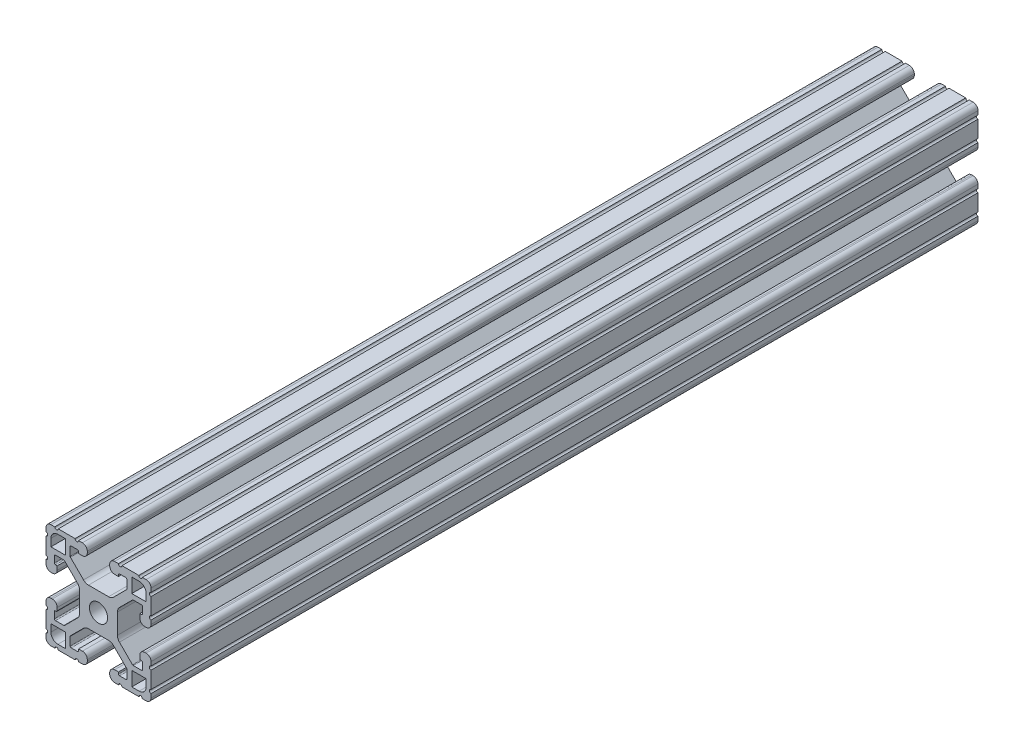
SolidWorks part; units mm, degrees
ref_plane "Front Plane" through (0, 0, 0) normal (0, 0, 1) x (1, 0, 0)
ref_plane "Top Plane" through (0, 0, 0) normal (0, 1, 0) x (1, 0, 0)
ref_plane "Right Plane" through (0, 0, 0) normal (1, 0, 0) x (0, 0, -1)
sketch "Sketch1" plane through (0, 0, 0) normal (0, 0, 1) x (1, 0, 0)
  line L0 (0, -19.05) -> (0, 19.05) construction
  line L1 (19.05, 0) -> (-19.05, 0) construction
  line L2 (4.064, 19.05) -> (-4.064, 19.05) construction
  line L3 (0, -6.858) -> (0, 6.858) construction
  line L4 (-4.064, 19.05) -> (-4.064, 14.986) construction
  line L5 (19.05, -10.287) -> (19.05, 10.287) construction
  line L6 (0, -3.302) -> (0, 3.302) construction
  point P4 (0, 0)
  point P8 (0, 0)
  point P11 (0, 19.05)
  point P14 (0, 0)
  point P18 (19.05, 0)
  point P21 (0, 0)
  dimension "Rail Width" = 38.1
  dimension "Rail Height" = 38.1
  dimension "T-Slot Width" = 8.128
  dimension "Thickness" = 4.064
  dimension "Opening Width" = 20.574
  dimension "Center Hole Diameter" = 6.604
  dimension "Slot Depth" = 12.192
sketch "Sketch2" plane through (0, 0, 0) normal (1, 0, 0) x (0, 0, -1)
  line L0 (-150.0188, 0) -> (150.0188, 0) construction
  line L1 (0, 19.05) -> (0, -19.05) construction
  line L2 (-25.4, 19.05) -> (25.4, 19.05) construction
  line L4 (3048, -19.05) -> (-3048, -19.05) construction
  point P0 (99.2188, 0)
  point P3 (-99.2188, 0)
  point P4 (0, 0)
  dimension "D1" = 50.8
  dimension "Rep Length" = 300.0375
  dimension "D2" = 50.8
  dimension "Length Range [Min]" = 50.8
  dimension "Length Range [Max]" = 6096
sketch "Sketch3" plane through (0, 0, 0) normal (0, 0, 1) x (1, 0, 0)
  line L1 (19.05, -19.05) -> (-19.05, -19.05)
  line L2 (19.05, -19.05) -> (19.05, 19.05)
  line L3 (19.05, 19.05) -> (-19.05, 19.05)
  line L4 (-19.05, -19.05) -> (-19.05, 19.05)
  line L5 (19.05, -19.05) -> (-19.05, 19.05) construction
  line L6 (19.05, 19.05) -> (-19.05, -19.05) construction
  point P0 (0, 0)
extrude "Boss-Extrude1" add sketch "Sketch3" along normal up to vertex (150.0188 mm away) and the other way up to vertex (150.0188 mm away) up to point (0, 0, 150.0188) other way up to point (0, 0, -150.0188)
sketch "Sketch4" plane through (0, 0, 150.0188) normal (0, 0, 1) x (1, 0, 0)
  line L4 (4.064, 14.986) -> (4.064, 19.05)
  line L5 (7.239, 14.986) -> (4.064, 14.986)
  line L6 (19.05, 0) -> (-19.05, 0) construction
  line L7 (4.7027, 6.858) -> (-4.7027, 6.858)
  line L8 (-4.7027, 6.858) -> (-10.287, 12.4423)
  line L37 (-19.05, 19.05) -> (-19.05, -19.05) construction
  line L38 (-19.05, -19.05) -> (19.05, -19.05) construction
  line L39 (-10.287, 12.4423) -> (-10.287, 16.002)
  line L40 (-10.287, 16.002) -> (-7.239, 16.002)
  line L41 (-7.239, 16.002) -> (-7.239, 14.986)
  line L42 (-7.239, 14.986) -> (-4.064, 14.986)
  line L43 (-4.064, 14.986) -> (-4.064, 19.05)
  line L44 (-4.064, 19.05) -> (4.064, 19.05)
  line L45 (0, 19.05) -> (0, 0) construction
  line L46 (-19.05, 19.05) -> (0, 0) construction
  line L47 (7.239, 16.002) -> (7.239, 14.986)
  line L48 (10.287, 16.002) -> (7.239, 16.002)
  line L49 (10.287, 12.4423) -> (10.287, 16.002)
  line L50 (4.7027, 6.858) -> (10.287, 12.4423)
  line L51 (-19.05, 0) -> (19.05, 0) construction
  line L52 (4.7027, -6.858) -> (10.287, -12.4423)
  line L53 (10.287, -12.4423) -> (10.287, -16.002)
  line L54 (10.287, -16.002) -> (7.239, -16.002)
  line L55 (7.239, -16.002) -> (7.239, -14.986)
  line L56 (-4.064, -19.05) -> (4.064, -19.05)
  line L57 (-4.064, -14.986) -> (-4.064, -19.05)
  line L58 (-7.239, -14.986) -> (-4.064, -14.986)
  line L59 (-7.239, -16.002) -> (-7.239, -14.986)
  line L60 (-10.287, -16.002) -> (-7.239, -16.002)
  line L61 (-10.287, -12.4423) -> (-10.287, -16.002)
  line L62 (-4.7027, -6.858) -> (-10.287, -12.4423)
  line L63 (4.7027, -6.858) -> (-4.7027, -6.858)
  line L64 (7.239, -14.986) -> (4.064, -14.986)
  line L65 (4.064, -14.986) -> (4.064, -19.05)
  line L66 (-6.858, -4.7027) -> (-12.4423, -10.287)
  line L67 (-12.4423, -10.287) -> (-16.002, -10.287)
  line L68 (-16.002, -10.287) -> (-16.002, -7.239)
  line L69 (-16.002, -7.239) -> (-14.986, -7.239)
  line L70 (-19.05, 4.064) -> (-19.05, -4.064)
  line L71 (-14.986, 4.064) -> (-19.05, 4.064)
  line L72 (-14.986, 7.239) -> (-14.986, 4.064)
  line L73 (-16.002, 7.239) -> (-14.986, 7.239)
  line L74 (-16.002, 10.287) -> (-16.002, 7.239)
  line L75 (-12.4423, 10.287) -> (-16.002, 10.287)
  line L76 (-6.858, 4.7027) -> (-12.4423, 10.287)
  line L77 (-6.858, -4.7027) -> (-6.858, 4.7027)
  line L78 (-14.986, -7.239) -> (-14.986, -4.064)
  line L79 (-14.986, -4.064) -> (-19.05, -4.064)
  line L80 (14.986, -4.064) -> (19.05, -4.064)
  line L81 (14.986, -7.239) -> (14.986, -4.064)
  line L82 (6.858, -4.7027) -> (6.858, 4.7027)
  line L83 (6.858, 4.7027) -> (12.4423, 10.287)
  line L84 (12.4423, 10.287) -> (16.002, 10.287)
  line L85 (16.002, 10.287) -> (16.002, 7.239)
  line L86 (16.002, 7.239) -> (14.986, 7.239)
  line L87 (14.986, 7.239) -> (14.986, 4.064)
  line L88 (14.986, 4.064) -> (19.05, 4.064)
  line L89 (19.05, 4.064) -> (19.05, -4.064)
  line L90 (16.002, -7.239) -> (14.986, -7.239)
  line L91 (16.002, -10.287) -> (16.002, -7.239)
  line L92 (12.4423, -10.287) -> (16.002, -10.287)
  line L93 (6.858, -4.7027) -> (12.4423, -10.287)
  line L94 (19.05, -19.05) -> (19.05, 19.05) construction
  line L95 (12.065, 17.272) -> (17.272, 17.272)
  line L96 (12.065, 17.272) -> (12.065, 12.065)
  line L97 (12.065, 12.065) -> (17.272, 12.065)
  line L98 (17.272, 17.272) -> (17.272, 12.065)
  line L99 (19.05, 19.05) -> (-19.05, 19.05) construction
  line L100 (17.272, -17.272) -> (17.272, -12.065)
  line L101 (12.065, -17.272) -> (17.272, -17.272)
  line L102 (12.065, -17.272) -> (12.065, -12.065)
  line L103 (12.065, -12.065) -> (17.272, -12.065)
  line L104 (-17.272, 17.272) -> (-17.272, 12.065)
  line L105 (-12.065, 12.065) -> (-17.272, 12.065)
  line L106 (-12.065, 17.272) -> (-12.065, 12.065)
  line L107 (-12.065, 17.272) -> (-17.272, 17.272)
  line L108 (-12.065, -12.065) -> (-17.272, -12.065)
  line L109 (-12.065, -17.272) -> (-12.065, -12.065)
  line L110 (-12.065, -17.272) -> (-17.272, -17.272)
  line L111 (-17.272, -17.272) -> (-17.272, -12.065)
  circle A5 centre (0, 0) radius 3.302
  point P21 (0, 6.858)
  point P23 (0, -6.858)
  point P38 (-6.858, 0)
  point P53 (6.858, 0)
  dimension "D1" = 20.574
  dimension "D2" = 3.048
  dimension "D3" = 3.048
  dimension "D4" = 3.048
  dimension "D5" = 1.778
  dimension "D6" = 1.778
  dimension "D7" = 1.778
extrude "Cut-Extrude1" cut sketch "Sketch4" against normal through all
sketch "Sketch5" plane through (0, 0, 150.0188) normal (0, 0, 1) x (1, 0, 0)
  line L4 (-4.064, 19.05) -> (-19.05, 19.05) construction
  line L26 (-19.05, 19.05) -> (-19.05, 4.064) construction
  line L27 (-15.875, 19.05) -> (-14.605, 19.05)
  line L28 (-8.509, 19.05) -> (-7.239, 19.05)
  line L29 (-19.05, 15.875) -> (-19.05, 14.605)
  line L30 (-19.05, 8.509) -> (-19.05, 7.239)
  line L31 (8.509, 19.05) -> (7.239, 19.05)
  line L32 (15.875, 19.05) -> (14.605, 19.05)
  line L33 (19.05, 15.875) -> (19.05, 14.605)
  line L34 (19.05, 8.509) -> (19.05, 7.239)
  line L35 (19.05, -8.509) -> (19.05, -7.239)
  line L36 (19.05, -15.875) -> (19.05, -14.605)
  line L37 (15.875, -19.05) -> (14.605, -19.05)
  line L38 (8.509, -19.05) -> (7.239, -19.05)
  line L39 (-8.509, -19.05) -> (-7.239, -19.05)
  line L40 (-15.875, -19.05) -> (-14.605, -19.05)
  line L41 (-19.05, -15.875) -> (-19.05, -14.605)
  line L42 (-19.05, -8.509) -> (-19.05, -7.239)
  line L43 (19.05, 19.05) -> (4.064, 19.05) construction
  line L44 (19.05, 4.064) -> (19.05, 19.05) construction
  line L48 (-14.986, 4.064) -> (-19.05, 4.064) construction
  line L49 (-4.064, 14.986) -> (-4.064, 19.05) construction
  arc A8 (-15.875, 19.05) -> (-14.605, 19.05) centre (-15.24, 19.05) ccw
  arc A9 (-8.509, 19.05) -> (-7.239, 19.05) centre (-7.874, 19.05) ccw
  arc A10 (-19.05, 14.605) -> (-19.05, 15.875) centre (-19.05, 15.24) ccw
  arc A11 (-19.05, 7.239) -> (-19.05, 8.509) centre (-19.05, 7.874) ccw
  arc A12 (7.239, 19.05) -> (8.509, 19.05) centre (7.874, 19.05) ccw
  arc A13 (14.605, 19.05) -> (15.875, 19.05) centre (15.24, 19.05) ccw
  arc A14 (19.05, 15.875) -> (19.05, 14.605) centre (19.05, 15.24) ccw
  arc A15 (19.05, 8.509) -> (19.05, 7.239) centre (19.05, 7.874) ccw
  arc A16 (19.05, -7.239) -> (19.05, -8.509) centre (19.05, -7.874) ccw
  arc A17 (19.05, -14.605) -> (19.05, -15.875) centre (19.05, -15.24) ccw
  arc A18 (15.875, -19.05) -> (14.605, -19.05) centre (15.24, -19.05) ccw
  arc A19 (8.509, -19.05) -> (7.239, -19.05) centre (7.874, -19.05) ccw
  arc A20 (-7.239, -19.05) -> (-8.509, -19.05) centre (-7.874, -19.05) ccw
  arc A21 (-14.605, -19.05) -> (-15.875, -19.05) centre (-15.24, -19.05) ccw
  arc A22 (-19.05, -15.875) -> (-19.05, -14.605) centre (-19.05, -15.24) ccw
  arc A23 (-19.05, -8.509) -> (-19.05, -7.239) centre (-19.05, -7.874) ccw
  dimension "D2" = 0.635
  dimension "D4" = 3.81
  dimension "D5" = 3.81
  dimension "D1" = 3.81
  dimension "D3" = 3.81
  dimension "D7" = 4
extrude "Cut-Extrude2" cut sketch "Sketch5" against normal through all
fillet "Fillet1" radius 2.54 12 edges at (-6.858, 4.7027, 0) (-6.858, -4.7027, 0) (4.7027, -6.858, 0) (-4.7027, -6.858, 0) (6.858, -4.7027, 0) (6.858, 4.7027, 0) (4.7027, 6.858, 0) (-4.7027, 6.858, 0) (-17.272, 17.272, 0) (17.272, 17.272, 0) (17.272, -17.272, 0) (-17.272, -17.272, 0)
fillet "Fillet2" radius 1.778 20 edges at (19.05, -19.05, 0) (19.05, 19.05, 0) (-19.05, -19.05, 0) (-19.05, 19.05, 0) (-14.986, 4.064, 0) (-19.05, 4.064, 0) (-19.05, -4.064, 0) (-14.986, -4.064, 0) (-4.064, -19.05, 0) (-4.064, -14.986, 0) (4.064, -14.986, 0) (4.064, -19.05, 0) (19.05, -4.064, 0) (14.986, -4.064, 0) (19.05, 4.064, 0) (14.986, 4.064, 0) (4.064, 14.986, 0) (4.064, 19.05, 0) (-4.064, 19.05, 0) (-4.064, 14.986, 0)
fillet "Fillet3" radius 0.3969 24 edges at (-14.986, -7.239, 0) (-16.002, -10.287, 0) (-12.4423, -10.287, 0) (-12.4423, 10.287, 0) (-16.002, 7.239, 0) (-16.002, 10.287, 0) (-10.287, 12.4423, 0) (-7.239, 16.002, 0) (-10.287, 16.002, 0) (10.287, 16.002, 0) (7.239, 16.002, 0) (10.287, 12.4423, 0) (16.002, 10.287, 0) (12.4423, 10.287, 0) (16.002, 7.239, 0) (16.002, -7.239, 0) (16.002, -10.287, 0) (12.4423, -10.287, 0) (10.287, -12.4423, 0) (10.287, -16.002, 0) (7.239, -16.002, 0) (-7.239, -16.002, 0) (-10.287, -12.4423, 0) (-10.287, -16.002, 0)
equation "\"D4@Sketch5\"=\"D3@Sketch5\""
equation "\"D5@Sketch5\"=\"D4@Sketch5\""
equation "\"D1@Sketch4\"=\"Opening Width@Sketch1\""
